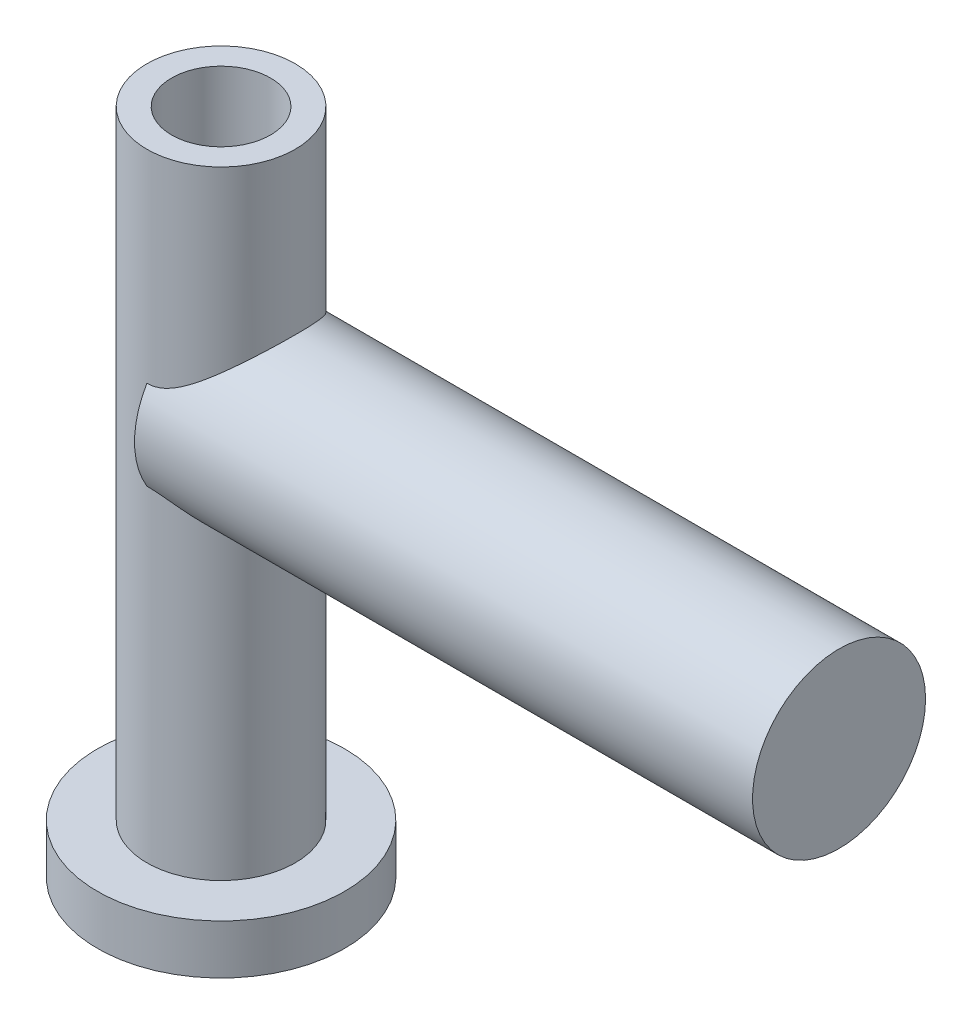
SolidWorks part; units mm, degrees
ref_plane "Front Plane" through (0, 0, 0) normal (0, 0, 1) x (1, 0, 0)
ref_plane "Top Plane" through (0, 0, 0) normal (0, 1, 0) x (1, 0, 0)
ref_plane "Right Plane" through (0, 0, 0) normal (1, 0, 0) x (0, 0, -1)
sketch "Sketch1" plane through (0, 0, 0) normal (0, 0, 1) x (1, 0, 0)
  line L0 (0, 0) -> (0, 270)
  line L1 (0, 270) -> (30, 270)
  line L2 (30, 270) -> (30, 20)
  line L3 (30, 20) -> (50, 20)
  line L4 (50, 20) -> (50, 0)
  line L5 (50, 0) -> (0, 0)
  dimension "D1" = 50
  dimension "D2" = 20
  dimension "D3" = 270
  dimension "D4" = 30
revolve "Revolve1" add sketch "Sketch1" angle 360 about L0
ref_plane "Plane1" through (0, 135, 0) normal (0, 1, 0) x (1, 0, 0)
sketch "Sketch2" plane through (0, 135, 0) normal (0, 1, 0) x (1, 0, 0)
  line L0 (-30, 0) -> (30, 0) construction
  circle A0 centre (0, 0) radius 30 construction
  point P7 (0, 0)
sketch "Sketch4" plane through (0, 270, 0) normal (0, 1, 0) x (1, 0, 0)
  circle A0 centre (0, 0) radius 20
  dimension "D1" = 40
extrude "Cut-Extrude1" cut sketch "Sketch4" against normal blind 300
sketch "Sketch5" plane through (0, 0, 0) normal (1, 0, 0) x (0, 0, -1)
  line L0 (30, 270) -> (-30, 270) construction
  line L1 (30, 20) -> (30, 270) construction
  circle A0 centre (0, 170) radius 35
  dimension "D1" = 70
  dimension "D2" = 100
  dimension "D3" = 30
extrude "Boss-Extrude1" add sketch "Sketch5" along normal blind 250
